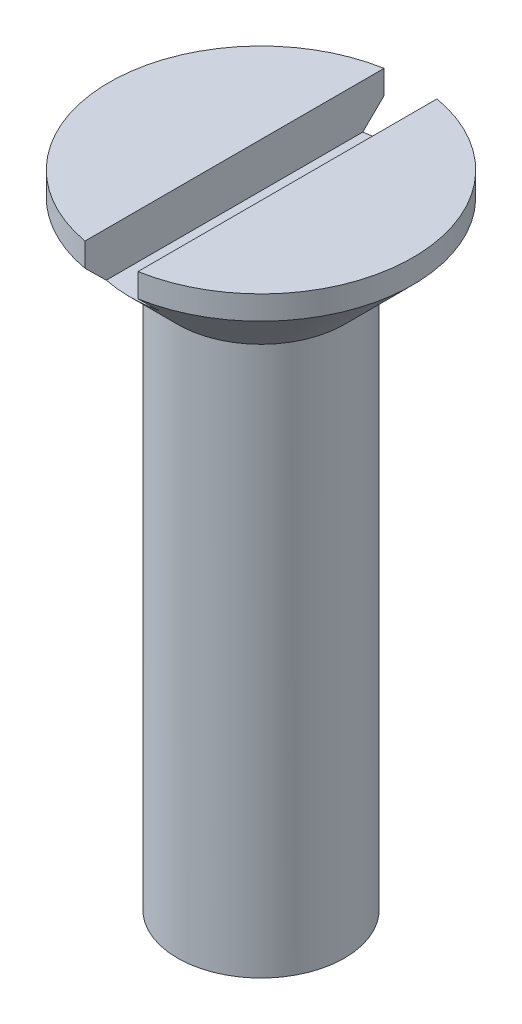
SolidWorks part; units mm, degrees
ref_plane "Front Plane" through (0, 0, 0) normal (0, 0, 1) x (1, 0, 0)
ref_plane "Top Plane" through (0, 0, 0) normal (0, 1, 0) x (1, 0, 0)
ref_plane "Right Plane" through (0, 0, 0) normal (1, 0, 0) x (0, 0, -1)
sketch "Sketch1" plane through (0, 0, 0) normal (0, 0, 1) x (1, 0, 0)
  line L0 (0, 0) -> (0, 50000) construction
  line L1 (0, 24.7321) -> (5.45, 24.7321)
  line L2 (5.45, 24.7321) -> (5.45, 23.8821)
  line L3 (5.45, 23.8821) -> (3, 21.4321)
  line L4 (3, 21.4321) -> (3, 1.7321)
  line L5 (3, 1.7321) -> (0, 0)
  line L6 (0, 0) -> (0, 24.7321)
  point P9 (0, 0)
  dimension "D1" = 45
  dimension "D2" = 3.3
  dimension "D3" = 6
  dimension "D4" = 23
  dimension "D5" = 60
  dimension "D6" = 10.9
revolve "Revolve1" add sketch "Sketch1" angle 360 about L0
sketch "Sketch2" plane through (0, 24.7321, 0) normal (0, 1, 0) x (1, 0, 0)
  line L1 (-0.95, 5.45) -> (0.95, 5.45)
  line L2 (-0.95, 5.45) -> (-0.95, -5.45)
  line L3 (-0.95, -5.45) -> (0.95, -5.45)
  line L4 (0.95, 5.45) -> (0.95, -5.45)
  line L5 (-0.95, 5.45) -> (0.95, -5.45) construction
  line L6 (-0.95, -5.45) -> (0.95, 5.45) construction
  circle A1 centre (0, 0) radius 5.45 construction
  point P0 (0, 0)
  dimension "D1" = 1.9
extrude "Cut-Extrude1" cut sketch "Sketch2" against normal blind 1.6
